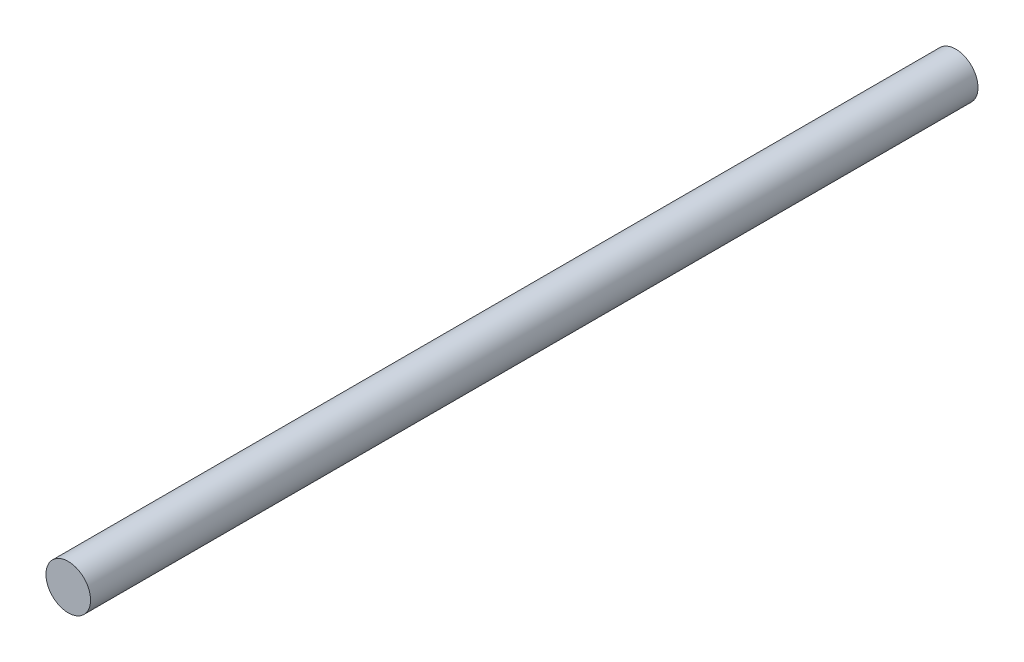
SolidWorks part; units mm, degrees
ref_plane "Front Plane" through (0, 0, 0) normal (0, 0, 1) x (1, 0, 0)
ref_plane "Top Plane" through (0, 0, 0) normal (0, 1, 0) x (1, 0, 0)
ref_plane "Right Plane" through (0, 0, 0) normal (1, 0, 0) x (0, 0, -1)
sketch "Sketch2" plane through (0, 0, 0) normal (0, 0, 1) x (1, 0, 0)
  circle A0 centre (0, 0) radius 1
  dimension "D1" = 2
extrude "Boss-Extrude1" add sketch "Sketch2" along normal blind 39.8018
